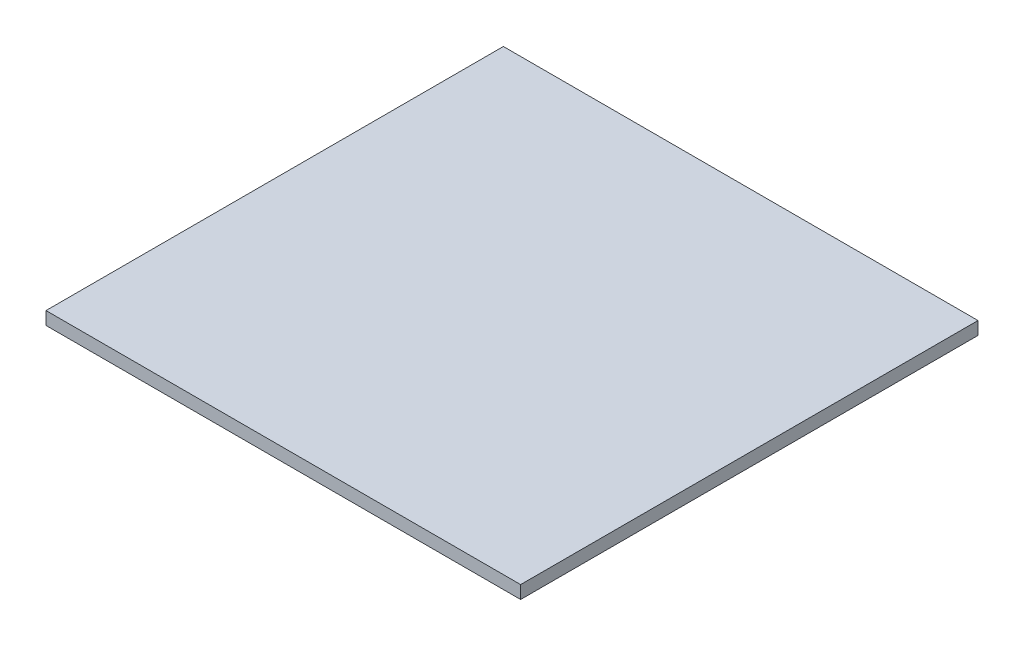
SolidWorks part; units mm, degrees
ref_plane "Front Plane" through (0, 0, 0) normal (0, 0, 1) x (1, 0, 0)
ref_plane "Top Plane" through (0, 0, 0) normal (0, 1, 0) x (1, 0, 0)
ref_plane "Right Plane" through (0, 0, 0) normal (1, 0, 0) x (0, 0, -1)
sketch "Sketch1" plane through (0, 0, 0) normal (0, 1, 0) x (1, 0, 0)
  line L1 (27.5, -26.5) -> (-27.5, -26.5)
  line L2 (27.5, -26.5) -> (27.5, 26.5)
  line L3 (27.5, 26.5) -> (-27.5, 26.5)
  line L4 (-27.5, -26.5) -> (-27.5, 26.5)
  line L5 (27.5, -26.5) -> (-27.5, 26.5) construction
  line L6 (27.5, 26.5) -> (-27.5, -26.5) construction
  point P0 (0, 0)
  dimension "D1" = 55
  dimension "D2" = 53
extrude "Boss-Extrude1" add sketch "Sketch1" along normal blind 1.5 contours L4 L3 L2 L1
